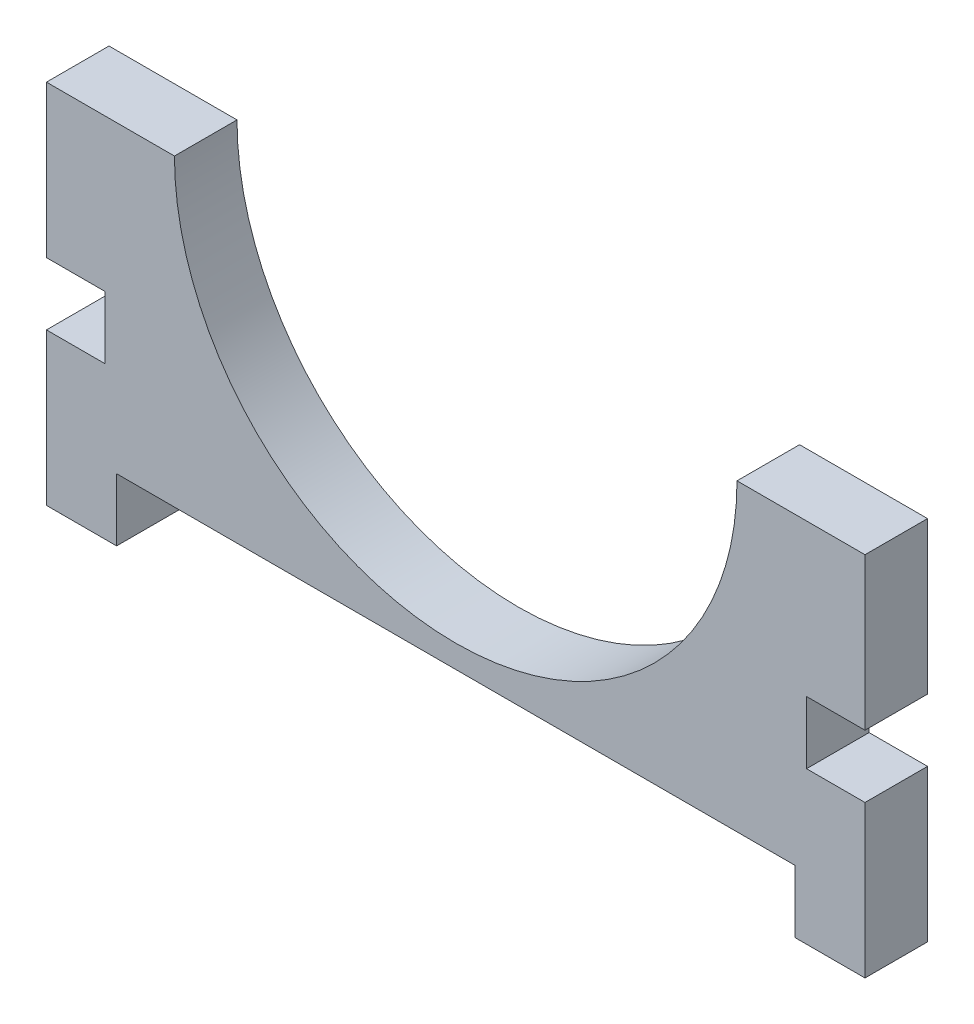
SolidWorks part; units mm, degrees
ref_plane "Front Plane" through (0, 0, 0) normal (0, 0, 1) x (1, 0, 0)
ref_plane "Top Plane" through (0, 0, 0) normal (0, 1, 0) x (1, 0, 0)
ref_plane "Right Plane" through (0, 0, 0) normal (1, 0, 0) x (0, 0, -1)
sketch "Model" plane through (0, 0, 0) normal (0, 0, 1) x (1, 0, 0)
  line L396 (70, 31.35) -> (59.055, 31.35)
  line L397 (70, 18.35) -> (70, 31.35)
  line L398 (65, 18.35) -> (70, 18.35)
  line L399 (65, 13) -> (65, 18.35)
  line L400 (70, 13) -> (65, 13)
  line L401 (70, 0) -> (70, 13)
  line L402 (64, 0) -> (70, 0)
  line L403 (64, 5.35) -> (64, 0)
  line L404 (6, 5.35) -> (64, 5.35)
  line L405 (6, 0) -> (6, 5.35)
  line L406 (0, 0) -> (6, 0)
  line L407 (0, 13) -> (0, 0)
  line L408 (5, 13) -> (0, 13)
  line L409 (5, 18.35) -> (5, 13)
  line L410 (0, 18.35) -> (5, 18.35)
  line L411 (0, 31.35) -> (0, 18.35)
  line L412 (10.945, 31.35) -> (0, 31.35)
  arc A56 (10.945, 31.35) -> (59.055, 31.35) centre (35, 31.35) ccw
extrude "Boss-Extrude1" add sketch "Model" along normal blind 5.35
